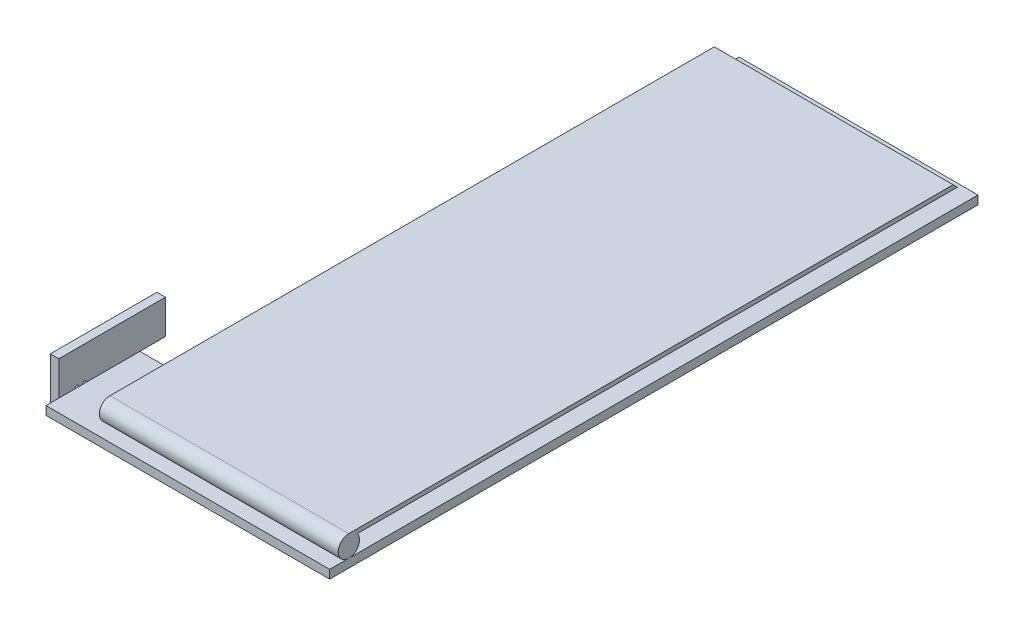
SolidWorks part; units mm, degrees
ref_plane "Front Plane" through (0, 0, 0) normal (0, 0, 1) x (1, 0, 0)
ref_plane "Top Plane" through (0, 0, 0) normal (0, 1, 0) x (1, 0, 0)
ref_plane "Right Plane" through (0, 0, 0) normal (1, 0, 0) x (0, 0, -1)
sketch "Sketch1" plane through (0, 0, 0) normal (0, 1, 0) x (1, 0, 0)
  line L0 (-30, -74.5) -> (-28, -74.5)
  line L1 (-28, -77.5) -> (38.5, -77.5)
  line L2 (-30, -74.5) -> (-30, -55.5)
  line L3 (-17.5032, 74.5) -> (38.5, 74.5)
  line L4 (38.5, -77.5) -> (38.5, 74.5)
  line L5 (-30, -55.5) -> (-17.5032, -55.5)
  line L6 (-17.5032, -55.5) -> (-17.5032, 74.5)
  line L7 (-28, -74.5) -> (-28, -77.5)
  dimension "D1" = 152
  dimension "D2" = 68.5
  dimension "D3" = 3
  dimension "D4" = 2
  dimension "D5" = 30
  dimension "D6" = 77.5
  dimension "D7" = 12.4968
  dimension "D8" = 130
extrude "Boss-Extrude1" add sketch "Sketch1" along normal blind 2
sketch "Sketch2" plane through (-30, 0, 0) normal (-1, 0, 0) x (0, 0, 1)
  line L0 (74.5, 2) -> (74.5, 10)
  line L1 (74.5, 10) -> (49.5, 10)
  line L2 (49.5, 10) -> (49.5, 2)
  line L3 (55.5, 2) -> (74.5, 2) construction
  line L4 (49.5, 2) -> (74.5, 2)
  line L5 (77.5, 2) -> (77.5, 0) construction
  dimension "D1" = 8
  dimension "D2" = 25
  dimension "D3" = 3
extrude "Boss-Extrude2" add sketch "Sketch2" against normal blind 2
sketch "Sketch3" plane through (-30, 0, 0) normal (-1, 0, 0) x (0, 0, 1)
  line L0 (55.5, 0) -> (74.5, 0) construction
  line L1 (74.5, 10) -> (74.5, 0) construction
  circle A0 centre (68.4555, 2.1345) radius 0.3618
  circle A1 centre (70.2644, 2.1345) radius 0.3618
  dimension "D1" = 0.7236
  dimension "D2" = 0.7236
  dimension "D3" = 2.1345
  dimension "D4" = 1.8089
  dimension "D5" = 4.2356
extrude "Cut-Extrude1" cut sketch "Sketch3" against normal up to surface (2 mm away) up to face at (-28, 5.2, 60.7)
ref_plane "Plane1" through (10.5, 0, 0) normal (1, 0, 0) x (0, 0, -1)
sketch "Sketch4" plane through (10.5, 0, 0) normal (1, 0, 0) x (0, 0, -1)
  line L0 (-77.5, 2) -> (-77.5, 0) construction
  line L1 (68.6716, 7) -> (69.6716, 6)
  line L3 (-55.5, 2) -> (-68.1196, 2) construction
  line L4 (-73, 7) -> (68.6716, 7)
  line L6 (69.6716, 6) -> (-71, 6)
  arc A0 (-73, 7) -> (-71, 6) centre (-73, 4.5) ccw
  dimension "D1" = 5
  dimension "D2" = 4.5
  dimension "D3" = 1
  dimension "D4" = 142.6716
  dimension "D5" = 45
extrude "Boss-Extrude4" add sketch "Sketch4" along normal mid plane 56 separate body
